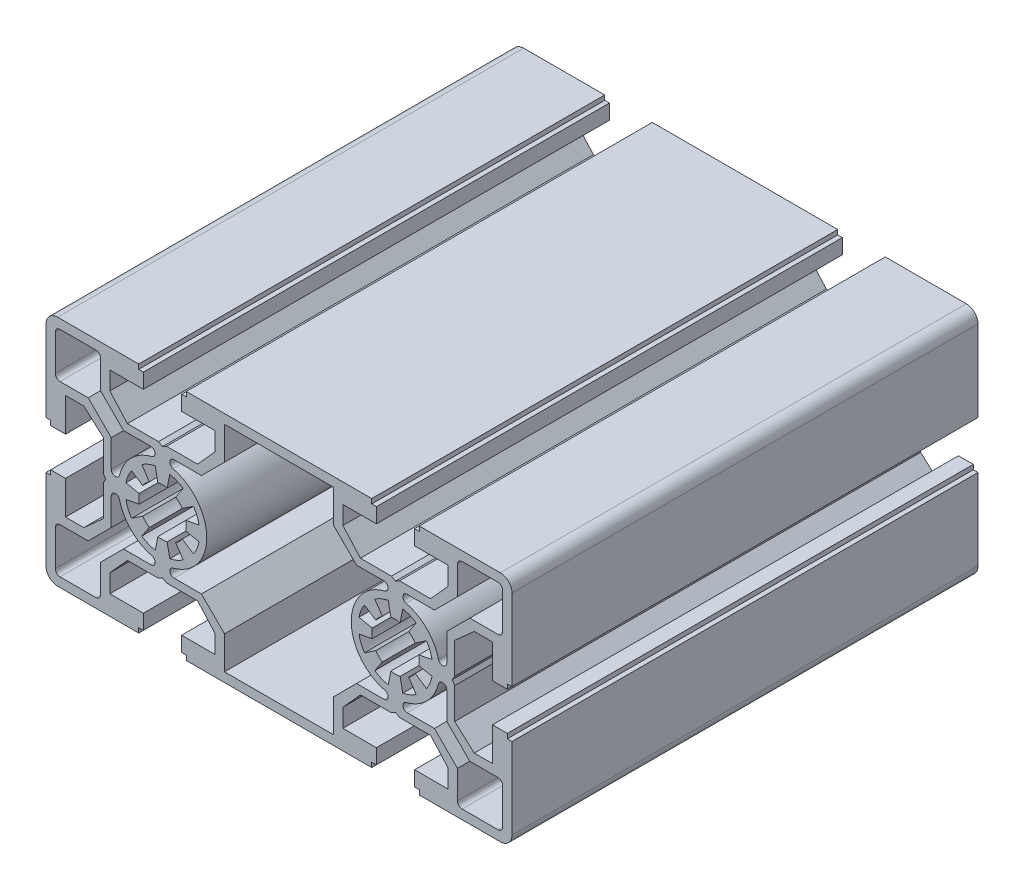
SolidWorks part; units mm, degrees
ref_plane "前视基准面" through (0, 0, 0) normal (0, 0, 1) x (1, 0, 0)
ref_plane "上视基准面" through (0, 0, 0) normal (0, 1, 0) x (1, 0, 0)
ref_plane "右视基准面" through (0, 0, 0) normal (1, 0, 0) x (0, 0, -1)
sketch "草图1" plane through (0, 0, 0) normal (0, 0, 1) x (1, 0, 0)
  line B0 (75, 5.1) -> (75, 22.5)
  line B1 (74, 5.1) -> (75, 5.1)
  line B2 (72.5, 25) -> (55.1, 25)
  line B3 (74, 4.1) -> (74, 5.1)
  line B4 (70.8, 4.1) -> (74, 4.1)
  line B5 (70.8, 11.3) -> (70.8, 4.1)
  line B6 (66.8898, 11.3) -> (70.8, 11.3)
  line B7 (62.7, 7.5302) -> (66.8898, 11.3)
  line B8 (62.7, 0.866) -> (62.7, 7.5302)
  line B9 (62.7, 0.866) -> (62.2, 0)
  line B10 (62.7, -0.866) -> (62.2, 0)
  line B11 (62.7, -7.5302) -> (62.7, -0.866)
  line B12 (66.8898, -11.3) -> (62.7, -7.5302)
  line B13 (70.8, -11.3) -> (66.8898, -11.3)
  line B14 (70.8, -4.1) -> (70.8, -11.3)
  line B15 (74, -4.1) -> (70.8, -4.1)
  line B16 (74, -5.1) -> (74, -4.1)
  line B17 (75, -5.1) -> (74, -5.1)
  line B18 (75, -22.5) -> (75, -5.1)
  line B19 (44.9, 25) -> (25, 25)
  line B20 (55.1, -25) -> (72.5, -25)
  line B21 (44.9, -25) -> (25, -25)
  line B22 (52.8334, 4.2405) -> (54.4446, 6.6518)
  line B23 (51.5607, 7.8463) -> (50.995, 5.002)
  line B24 (49.005, 5.002) -> (48.4393, 7.8463)
  line B25 (45.5554, 6.6518) -> (47.1666, 4.2405)
  line B26 (45.7595, 2.8334) -> (43.3482, 4.4446)
  line B27 (42.1537, 1.5607) -> (44.998, 0.995)
  line B28 (44.998, -0.995) -> (42.1537, -1.5607)
  line B29 (43.3482, -4.4446) -> (45.7595, -2.8334)
  line B30 (47.1666, -4.2405) -> (45.5554, -6.6518)
  line B31 (48.4393, -7.8463) -> (49.005, -5.002)
  line B32 (50.995, -5.002) -> (51.5607, -7.8463)
  line B33 (54.4446, -6.6518) -> (52.8334, -4.2405)
  line B34 (54.2405, -2.8334) -> (56.6518, -4.4446)
  line B35 (57.8463, -1.5607) -> (55.002, -0.995)
  line B36 (55.002, 0.995) -> (57.8463, 1.5607)
  line B37 (56.6518, 4.4446) -> (54.2405, 2.8334)
  line B38 (65.9414, 13.3) -> (61, 8.3586)
  line B39 (61, 8.3586) -> (61, 2.4799)
  line B40 (72, 13.3) -> (65.9414, 13.3)
  line B41 (73, 22) -> (73, 14.3)
  line B42 (52.4799, 11) -> (58.3586, 11)
  line B43 (64.3, 23) -> (72, 23)
  line B44 (58.3586, 11) -> (63.3, 15.9414)
  line B45 (63.3, 15.9414) -> (63.3, 22)
  line B46 (25, 23) -> (36.7, 23)
  line B47 (44.9, 24) -> (44.9, 25)
  line B48 (45.9, 24) -> (44.9, 24)
  line B49 (45.9, 20.8) -> (45.9, 24)
  line B50 (38.7, 20.8) -> (45.9, 20.8)
  line B51 (38.7, 16.8898) -> (38.7, 20.8)
  line B52 (42.4698, 12.7) -> (38.7, 16.8898)
  line B53 (49.134, 12.7) -> (42.4698, 12.7)
  line B54 (49.134, 12.7) -> (50, 12.2)
  line B55 (50.866, 12.7) -> (50, 12.2)
  line B56 (57.5302, 12.7) -> (50.866, 12.7)
  line B57 (61.3, 16.8898) -> (57.5302, 12.7)
  line B58 (61.3, 20.8) -> (61.3, 16.8898)
  line B59 (54.1, 20.8) -> (61.3, 20.8)
  line B60 (54.1, 24) -> (54.1, 20.8)
  line B61 (55.1, 24) -> (54.1, 24)
  line B62 (55.1, 25) -> (55.1, 24)
  line B63 (55.1, -24) -> (55.1, -25)
  line B64 (54.1, -24) -> (55.1, -24)
  line B65 (54.1, -20.8) -> (54.1, -24)
  line B66 (61.3, -20.8) -> (54.1, -20.8)
  line B67 (61.3, -16.8898) -> (61.3, -20.8)
  line B68 (57.5302, -12.7) -> (61.3, -16.8898)
  line B69 (50.866, -12.7) -> (57.5302, -12.7)
  line B70 (50.866, -12.7) -> (50, -12.2)
  line B71 (49.134, -12.7) -> (50, -12.2)
  line B72 (42.4698, -12.7) -> (49.134, -12.7)
  line B73 (38.7, -16.8898) -> (42.4698, -12.7)
  line B74 (38.7, -20.8) -> (38.7, -16.8898)
  line B75 (45.9, -20.8) -> (38.7, -20.8)
  line B76 (45.9, -24) -> (45.9, -20.8)
  line B77 (44.9, -24) -> (45.9, -24)
  line B78 (44.9, -25) -> (44.9, -24)
  line B79 (65.9414, -13.3) -> (61, -8.3586)
  line B80 (61, -8.3586) -> (61, -2.4799)
  line B81 (72, -13.3) -> (65.9414, -13.3)
  line B82 (73, -22) -> (73, -14.3)
  line B83 (52.4799, -11) -> (58.3586, -11)
  line B84 (64.3, -23) -> (72, -23)
  line B85 (58.3586, -11) -> (63.3, -15.9414)
  line B86 (63.3, -15.9414) -> (63.3, -22)
  line B87 (47.5201, 11) -> (41.6414, 11)
  line B88 (47.5201, -11) -> (41.6414, -11)
  line B89 (41.6414, 11) -> (36.7, 15.9414)
  line B90 (36.7, 15.9414) -> (36.7, 23)
  line B91 (25, -23) -> (36.7, -23)
  line B92 (36.7, -15.9414) -> (36.7, -23)
  line B93 (41.6414, -11) -> (36.7, -15.9414)
  line B94 (-25, 5.1) -> (-25, 22.5)
  line B95 (-24, 5.1) -> (-25, 5.1)
  line B96 (-22.5, 25) -> (-5.1, 25)
  line B97 (-24, 4.1) -> (-24, 5.1)
  line B98 (-20.8, 4.1) -> (-24, 4.1)
  line B99 (-20.8, 11.3) -> (-20.8, 4.1)
  line B100 (-16.8898, 11.3) -> (-20.8, 11.3)
  line B101 (-12.7, 7.5302) -> (-16.8898, 11.3)
  line B102 (-12.7, 0.866) -> (-12.7, 7.5302)
  line B103 (-12.7, 0.866) -> (-12.2, 0)
  line B104 (-12.7, -0.866) -> (-12.2, 0)
  line B105 (-12.7, -7.5302) -> (-12.7, -0.866)
  line B106 (-16.8898, -11.3) -> (-12.7, -7.5302)
  line B107 (-20.8, -11.3) -> (-16.8898, -11.3)
  line B108 (-20.8, -4.1) -> (-20.8, -11.3)
  line B109 (-24, -4.1) -> (-20.8, -4.1)
  line B110 (-24, -5.1) -> (-24, -4.1)
  line B111 (-25, -5.1) -> (-24, -5.1)
  line B112 (-25, -22.5) -> (-25, -5.1)
  line B113 (5.1, 25) -> (25, 25)
  line B114 (-5.1, -25) -> (-22.5, -25)
  line B115 (5.1, -25) -> (25, -25)
  line B116 (-4.2405, 2.8334) -> (-6.6518, 4.4446)
  line B117 (-7.8463, 1.5607) -> (-5.002, 0.995)
  line B118 (-5.002, -0.995) -> (-7.8463, -1.5607)
  line B119 (-6.6518, -4.4446) -> (-4.2405, -2.8334)
  line B120 (-2.8334, -4.2405) -> (-4.4446, -6.6518)
  line B121 (-1.5607, -7.8463) -> (-0.995, -5.002)
  line B122 (0.995, -5.002) -> (1.5607, -7.8463)
  line B123 (4.4446, -6.6518) -> (2.8334, -4.2405)
  line B124 (4.2405, -2.8334) -> (6.6518, -4.4446)
  line B125 (7.8463, -1.5607) -> (5.002, -0.995)
  line B126 (5.002, 0.995) -> (7.8463, 1.5607)
  line B127 (6.6518, 4.4446) -> (4.2405, 2.8334)
  line B128 (2.8334, 4.2405) -> (4.4446, 6.6518)
  line B129 (1.5607, 7.8463) -> (0.995, 5.002)
  line B130 (-0.995, 5.002) -> (-1.5607, 7.8463)
  line B131 (-4.4446, 6.6518) -> (-2.8334, 4.2405)
  line B132 (-15.9414, 13.3) -> (-11, 8.3586)
  line B133 (-11, 8.3586) -> (-11, 2.4799)
  line B134 (-22, 13.3) -> (-15.9414, 13.3)
  line B135 (-23, 22) -> (-23, 14.3)
  line B136 (-2.4799, 11) -> (-8.3586, 11)
  line B137 (-14.3, 23) -> (-22, 23)
  line B138 (-8.3586, 11) -> (-13.3, 15.9414)
  line B139 (-13.3, 15.9414) -> (-13.3, 22)
  line B140 (25, 23) -> (13.3, 23)
  line B141 (5.1, 24) -> (5.1, 25)
  line B142 (4.1, 24) -> (5.1, 24)
  line B143 (4.1, 20.8) -> (4.1, 24)
  line B144 (11.3, 20.8) -> (4.1, 20.8)
  line B145 (11.3, 16.8898) -> (11.3, 20.8)
  line B146 (7.5302, 12.7) -> (11.3, 16.8898)
  line B147 (0.866, 12.7) -> (7.5302, 12.7)
  line B148 (0.866, 12.7) -> (0, 12.2)
  line B149 (-0.866, 12.7) -> (0, 12.2)
  line B150 (-7.5302, 12.7) -> (-0.866, 12.7)
  line B151 (-11.3, 16.8898) -> (-7.5302, 12.7)
  line B152 (-11.3, 20.8) -> (-11.3, 16.8898)
  line B153 (-4.1, 20.8) -> (-11.3, 20.8)
  line B154 (-4.1, 24) -> (-4.1, 20.8)
  line B155 (-5.1, 24) -> (-4.1, 24)
  line B156 (-5.1, 25) -> (-5.1, 24)
  line B157 (-5.1, -24) -> (-5.1, -25)
  line B158 (-4.1, -24) -> (-5.1, -24)
  line B159 (-4.1, -20.8) -> (-4.1, -24)
  line B160 (-11.3, -20.8) -> (-4.1, -20.8)
  line B161 (-11.3, -16.8898) -> (-11.3, -20.8)
  line B162 (-7.5302, -12.7) -> (-11.3, -16.8898)
  line B163 (-0.866, -12.7) -> (-7.5302, -12.7)
  line B164 (-0.866, -12.7) -> (0, -12.2)
  line B165 (0.866, -12.7) -> (0, -12.2)
  line B166 (7.5302, -12.7) -> (0.866, -12.7)
  line B167 (11.3, -16.8898) -> (7.5302, -12.7)
  line B168 (11.3, -20.8) -> (11.3, -16.8898)
  line B169 (4.1, -20.8) -> (11.3, -20.8)
  line B170 (4.1, -24) -> (4.1, -20.8)
  line B171 (5.1, -24) -> (4.1, -24)
  line B172 (5.1, -25) -> (5.1, -24)
  line B173 (-15.9414, -13.3) -> (-11, -8.3586)
  line B174 (-11, -8.3586) -> (-11, -2.4799)
  line B175 (-22, -13.3) -> (-15.9414, -13.3)
  line B176 (-23, -22) -> (-23, -14.3)
  line B177 (-2.4799, -11) -> (-8.3586, -11)
  line B178 (-14.3, -23) -> (-22, -23)
  line B179 (-8.3586, -11) -> (-13.3, -15.9414)
  line B180 (-13.3, -15.9414) -> (-13.3, -22)
  line B181 (2.4799, 11) -> (8.3586, 11)
  line B182 (2.4799, -11) -> (8.3586, -11)
  line B183 (8.3586, 11) -> (13.3, 15.9414)
  line B184 (13.3, 15.9414) -> (13.3, 23)
  line B185 (25, -23) -> (13.3, -23)
  line B186 (13.3, -15.9414) -> (13.3, -23)
  line B187 (8.3586, -11) -> (13.3, -15.9414)
  arc B188 (75, 22.5) -> (72.5, 25) centre (72.5, 22.5) ccw
  arc B189 (72.5, -25) -> (75, -22.5) centre (72.5, -22.5) ccw
  arc B190 (54.2405, 2.8334) -> (52.8334, 4.2405) centre (50, 0) ccw
  arc B191 (54.4446, 6.6518) -> (51.5607, 7.8463) centre (50, 0) ccw
  arc B192 (50.995, 5.002) -> (49.005, 5.002) centre (50, 0) ccw
  arc B193 (48.4393, 7.8463) -> (45.5554, 6.6518) centre (50, 0) ccw
  arc B194 (47.1666, 4.2405) -> (45.7595, 2.8334) centre (50, 0) ccw
  arc B195 (43.3482, 4.4446) -> (42.1537, 1.5607) centre (50, 0) ccw
  arc B196 (44.998, 0.995) -> (44.998, -0.995) centre (50, 0) ccw
  arc B197 (42.1537, -1.5607) -> (43.3482, -4.4446) centre (50, 0) ccw
  arc B198 (45.7595, -2.8334) -> (47.1666, -4.2405) centre (50, 0) ccw
  arc B199 (45.5554, -6.6518) -> (48.4393, -7.8463) centre (50, 0) ccw
  arc B200 (49.005, -5.002) -> (50.995, -5.002) centre (50, 0) ccw
  arc B201 (51.5607, -7.8463) -> (54.4446, -6.6518) centre (50, 0) ccw
  arc B202 (52.8334, -4.2405) -> (54.2405, -2.8334) centre (50, 0) ccw
  arc B203 (56.6518, -4.4446) -> (57.8463, -1.5607) centre (50, 0) ccw
  arc B204 (55.002, -0.995) -> (55.002, 0.995) centre (50, 0) ccw
  arc B205 (57.8463, 1.5607) -> (56.6518, 4.4446) centre (50, 0) ccw
  arc B206 (59.226, 2.2653) -> (61, 2.4799) centre (60.1, 2.4799) ccw
  arc B207 (72, 13.3) -> (73, 14.3) centre (72, 14.3) ccw
  arc B208 (59.226, 2.2653) -> (52.2653, 9.226) centre (50, 0) ccw
  arc B209 (52.4799, 11) -> (52.2653, 9.226) centre (52.4799, 10.1) ccw
  arc B210 (73, 22) -> (72, 23) centre (72, 22) ccw
  arc B211 (64.3, 23) -> (63.3, 22) centre (64.3, 22) ccw
  arc B212 (47.7347, 9.226) -> (40.774, 2.2653) centre (50, 0) ccw
  arc B213 (40.774, 2.2653) -> (47.7347, -9.226) centre (50, 0) ccw
  arc B214 (47.7347, 9.226) -> (47.5201, 11) centre (47.5201, 10.1) ccw
  arc B215 (61, -2.4799) -> (59.226, -2.2653) centre (60.1, -2.4799) ccw
  arc B216 (73, -14.3) -> (72, -13.3) centre (72, -14.3) ccw
  arc B217 (52.2653, -9.226) -> (59.226, -2.2653) centre (50, 0) ccw
  arc B218 (52.2653, -9.226) -> (52.4799, -11) centre (52.4799, -10.1) ccw
  arc B219 (72, -23) -> (73, -22) centre (72, -22) ccw
  arc B220 (63.3, -22) -> (64.3, -23) centre (64.3, -22) ccw
  arc B221 (47.5201, -11) -> (47.7347, -9.226) centre (47.5201, -10.1) ccw
  arc B222 (-22.5, 25) -> (-25, 22.5) centre (-22.5, 22.5) ccw
  arc B223 (-25, -22.5) -> (-22.5, -25) centre (-22.5, -22.5) ccw
  arc B224 (-2.8334, 4.2405) -> (-4.2405, 2.8334) centre (0, 0) ccw
  arc B225 (-6.6518, 4.4446) -> (-7.8463, 1.5607) centre (0, 0) ccw
  arc B226 (-5.002, 0.995) -> (-5.002, -0.995) centre (0, 0) ccw
  arc B227 (-7.8463, -1.5607) -> (-6.6518, -4.4446) centre (0, 0) ccw
  arc B228 (-4.2405, -2.8334) -> (-2.8334, -4.2405) centre (0, 0) ccw
  arc B229 (-4.4446, -6.6518) -> (-1.5607, -7.8463) centre (0, 0) ccw
  arc B230 (-0.995, -5.002) -> (0.995, -5.002) centre (0, 0) ccw
  arc B231 (1.5607, -7.8463) -> (4.4446, -6.6518) centre (0, 0) ccw
  arc B232 (2.8334, -4.2405) -> (4.2405, -2.8334) centre (0, 0) ccw
  arc B233 (6.6518, -4.4446) -> (7.8463, -1.5607) centre (0, 0) ccw
  arc B234 (5.002, -0.995) -> (5.002, 0.995) centre (0, 0) ccw
  arc B235 (7.8463, 1.5607) -> (6.6518, 4.4446) centre (0, 0) ccw
  arc B236 (4.2405, 2.8334) -> (2.8334, 4.2405) centre (0, 0) ccw
  arc B237 (4.4446, 6.6518) -> (1.5607, 7.8463) centre (0, 0) ccw
  arc B238 (0.995, 5.002) -> (-0.995, 5.002) centre (0, 0) ccw
  arc B239 (-1.5607, 7.8463) -> (-4.4446, 6.6518) centre (0, 0) ccw
  arc B240 (-11, 2.4799) -> (-9.226, 2.2653) centre (-10.1, 2.4799) ccw
  arc B241 (-23, 14.3) -> (-22, 13.3) centre (-22, 14.3) ccw
  arc B242 (-2.2653, 9.226) -> (-9.226, 2.2653) centre (0, 0) ccw
  arc B243 (-2.2653, 9.226) -> (-2.4799, 11) centre (-2.4799, 10.1) ccw
  arc B244 (-22, 23) -> (-23, 22) centre (-22, 22) ccw
  arc B245 (-13.3, 22) -> (-14.3, 23) centre (-14.3, 22) ccw
  arc B246 (9.226, 2.2653) -> (2.2653, 9.226) centre (0, 0) ccw
  arc B247 (2.2653, -9.226) -> (9.226, 2.2653) centre (0, 0) ccw
  arc B248 (2.4799, 11) -> (2.2653, 9.226) centre (2.4799, 10.1) ccw
  arc B249 (-9.226, -2.2653) -> (-11, -2.4799) centre (-10.1, -2.4799) ccw
  arc B250 (-22, -13.3) -> (-23, -14.3) centre (-22, -14.3) ccw
  arc B251 (-9.226, -2.2653) -> (-2.2653, -9.226) centre (0, 0) ccw
  arc B252 (-2.4799, -11) -> (-2.2653, -9.226) centre (-2.4799, -10.1) ccw
  arc B253 (-23, -22) -> (-22, -23) centre (-22, -22) ccw
  arc B254 (-14.3, -23) -> (-13.3, -22) centre (-14.3, -22) ccw
  arc B255 (2.2653, -9.226) -> (2.4799, -11) centre (2.4799, -10.1) ccw
sketch_block_instance "A$C3E736FB3-1"
sketch_block "A$C3E736FB3"
extrude "凸台-拉伸1" add sketch "草图1" along normal blind 100
